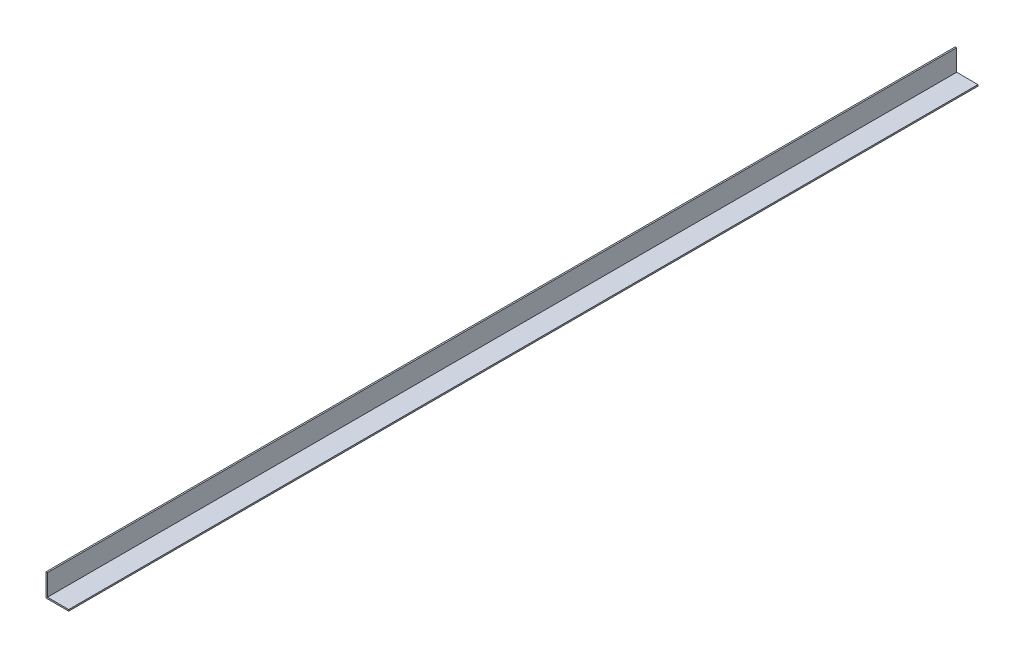
SolidWorks part; units mm, degrees
ref_plane "Front Plane" through (0, 0, 0) normal (0, 0, 1) x (1, 0, 0)
ref_plane "Top Plane" through (0, 0, 0) normal (0, 1, 0) x (1, 0, 0)
ref_plane "Right Plane" through (0, 0, 0) normal (1, 0, 0) x (0, 0, -1)
sketch "Sketch1" plane through (0, 0, 0) normal (0, 0, 1) x (1, 0, 0)
  line L1 (0, 0) -> (25.4, 0)
  line L2 (0, 0) -> (0, 25.4)
  line L3 (0, 25.4) -> (25.4, 25.4)
  line L4 (25.4, 0) -> (25.4, 25.4)
  line L5 (25.4, 25.4) -> (1.5875, 25.4)
  line L6 (25.4, 25.4) -> (25.4, 1.5875)
  line L7 (25.4, 1.5875) -> (1.5875, 1.5875)
  line L8 (1.5875, 25.4) -> (1.5875, 1.5875)
  dimension "D1" = 25.4
  dimension "D2" = 25.4
  dimension "D3" = 1.5875
  dimension "D4" = 1.5875
extrude "Boss-Extrude1" add sketch "Sketch1" along normal blind 1016 contours L8 L3 L2 L1 L4 L7
